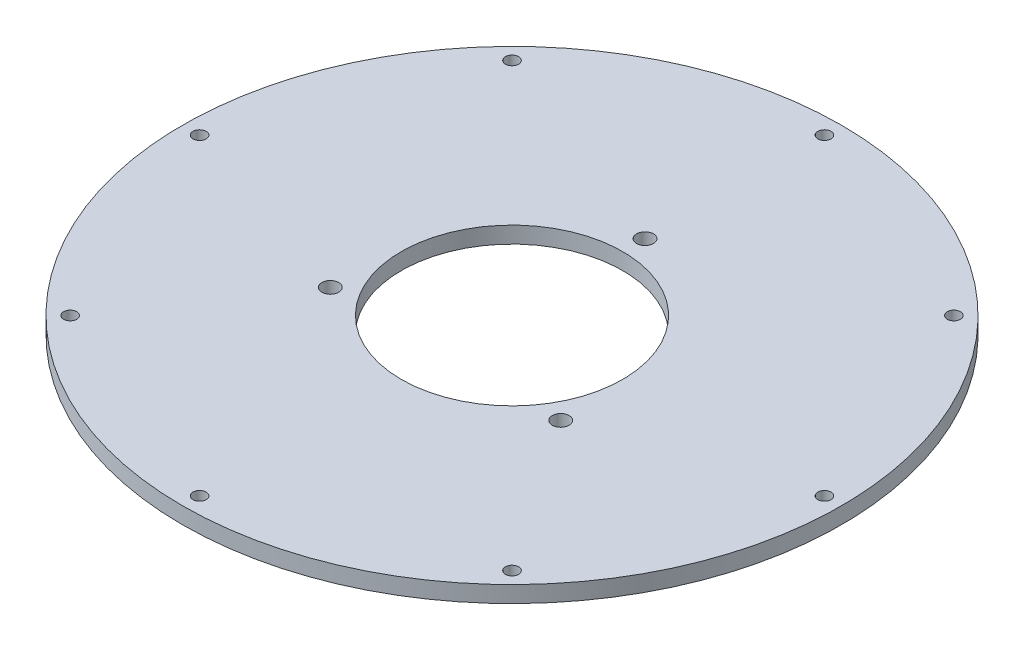
SolidWorks part; units mm, degrees
ref_plane "Front Plane" through (0, 0, 0) normal (0, 0, 1) x (1, 0, 0)
ref_plane "Top Plane" through (0, 0, 0) normal (0, 1, 0) x (1, 0, 0)
ref_plane "Right Plane" through (0, 0, 0) normal (1, 0, 0) x (0, 0, -1)
sketch "Sketch1" plane through (0, 0, 0) normal (0, 1, 0) x (1, 0, 0)
  circle A0 centre (0, 0) radius 62.5
  circle A1 centre (0, 0) radius 21
  circle A2 centre (0, 0) radius 21 construction
  dimension "D1" = 0
  dimension "D2" = 125
extrude "Boss-Extrude1" add sketch "Sketch1" along normal blind 3.125
sketch "Sketch2" plane through (0, 3.125, 0) normal (0, 1, 0) x (1, 0, 0)
  line L0 (0, 25.225) -> (0, 0) construction
  circle A0 centre (0, 25.225) radius 1.6
  circle A1 centre (21.8455, -12.6125) radius 1.6
  circle A2 centre (-21.8455, -12.6125) radius 1.6
  point P10 (0, 0)
  dimension "D2" = 3.2
  dimension "D3" = 3
extrude "Cut-Extrude1" cut sketch "Sketch2" against normal through all
sketch "Sketch5" plane through (0, 3.125, 0) normal (0, 1, 0) x (1, 0, 0)
  line L0 (3, 45.7275) -> (3, 31.607)
  line L1 (38.1011, 25.4618) -> (25.8724, 18.4016)
  line L2 (0, 0) -> (0, 62.5) construction
  line L3 (41.1011, -20.2657) -> (28.8724, -13.2054)
  line L4 (41.1011, 20.2657) -> (28.8724, 13.2054)
  line L5 (3, -45.7275) -> (3, -31.607)
  line L6 (38.1011, -25.4618) -> (25.8724, -18.4016)
  line L7 (-38.1011, -25.4618) -> (-25.8724, -18.4016)
  line L8 (-3, -45.7275) -> (-3, -31.607)
  line L9 (-41.1011, 20.2657) -> (-28.8724, 13.2054)
  line L10 (-41.1011, -20.2657) -> (-28.8724, -13.2054)
  line L11 (-3, 45.7275) -> (-3, 31.607)
  line L12 (-38.1011, 25.4618) -> (-25.8724, 18.4016)
  line L13 (3, 46.1306) -> (-3, 46.1306) construction
  circle A0 centre (0, 0) radius 62.5 construction
  arc A1 (4.6875, 29.6315) -> (23.3179, 18.8753) centre (0, 0) cw
  arc A2 (5.2174, 47.7156) -> (38.7142, 28.3762) centre (0, 0) cw
  arc A3 (38.7142, 28.3762) -> (38.1011, 25.4618) centre (37.1011, 27.1939) cw
  arc A4 (3, 45.7275) -> (5.2174, 47.7156) centre (5, 45.7275) cw
  arc A5 (23.3179, 18.8753) -> (25.8724, 18.4016) centre (24.8724, 20.1336) ccw
  arc A6 (3, 31.607) -> (4.6875, 29.6315) centre (5, 31.607) ccw
  arc A7 (28.0054, -10.7563) -> (28.8724, -13.2054) centre (29.8724, -11.4734) ccw
  arc A8 (43.9316, -19.3394) -> (41.1011, -20.2657) centre (42.1011, -18.5336) cw
  arc A9 (28.0054, 10.7563) -> (28.0054, -10.7563) centre (0, 0) cw
  arc A10 (28.8724, 13.2054) -> (28.0054, 10.7563) centre (29.8724, 11.4734) ccw
  arc A11 (41.1011, 20.2657) -> (43.9316, 19.3394) centre (42.1011, 18.5336) cw
  arc A12 (43.9316, 19.3394) -> (43.9316, -19.3394) centre (0, 0) cw
  arc A13 (4.6875, -29.6315) -> (3, -31.607) centre (5, -31.607) ccw
  arc A14 (5.2174, -47.7156) -> (3, -45.7275) centre (5, -45.7275) cw
  arc A15 (23.3179, -18.8753) -> (4.6875, -29.6315) centre (0, 0) cw
  arc A16 (25.8724, -18.4016) -> (23.3179, -18.8753) centre (24.8724, -20.1336) ccw
  arc A17 (38.1011, -25.4618) -> (38.7142, -28.3762) centre (37.1011, -27.1939) cw
  arc A18 (38.7142, -28.3762) -> (5.2174, -47.7156) centre (0, 0) cw
  arc A19 (-23.3179, -18.8753) -> (-25.8724, -18.4016) centre (-24.8724, -20.1336) ccw
  arc A20 (-38.7142, -28.3762) -> (-38.1011, -25.4618) centre (-37.1011, -27.1939) cw
  arc A21 (-4.6875, -29.6315) -> (-23.3179, -18.8753) centre (0, 0) cw
  arc A22 (-3, -31.607) -> (-4.6875, -29.6315) centre (-5, -31.607) ccw
  arc A23 (-3, -45.7275) -> (-5.2174, -47.7156) centre (-5, -45.7275) cw
  arc A24 (-5.2174, -47.7156) -> (-38.7142, -28.3762) centre (0, 0) cw
  arc A25 (-28.0054, 10.7563) -> (-28.8724, 13.2054) centre (-29.8724, 11.4734) ccw
  arc A26 (-43.9316, 19.3394) -> (-41.1011, 20.2657) centre (-42.1011, 18.5336) cw
  arc A27 (-28.0054, -10.7563) -> (-28.0054, 10.7563) centre (0, 0) cw
  arc A28 (-28.8724, -13.2054) -> (-28.0054, -10.7563) centre (-29.8724, -11.4734) ccw
  arc A29 (-41.1011, -20.2657) -> (-43.9316, -19.3394) centre (-42.1011, -18.5336) cw
  arc A30 (-43.9316, -19.3394) -> (-43.9316, 19.3394) centre (0, 0) cw
  arc A31 (-4.6875, 29.6315) -> (-3, 31.607) centre (-5, 31.607) ccw
  arc A32 (-5.2174, 47.7156) -> (-3, 45.7275) centre (-5, 45.7275) cw
  arc A33 (-23.3179, 18.8753) -> (-4.6875, 29.6315) centre (0, 0) cw
  arc A34 (-25.8724, 18.4016) -> (-23.3179, 18.8753) centre (-24.8724, 20.1336) ccw
  arc A35 (-38.1011, 25.4618) -> (-38.7142, 28.3762) centre (-37.1011, 27.1939) cw
  arc A36 (-38.7142, 28.3762) -> (-5.2174, 47.7156) centre (0, 0) cw
  point P80 (0, 0)
  point P82 (0, 46.1306)
  dimension "D1" = 2
  dimension "D4" = 30
  dimension "D5" = 48
  dimension "D3" = 6
  dimension "D2" = 6
extrude "Cut-Extrude2" [suppressed] cut sketch "Sketch5" against normal through all
sketch "Sketch6" plane through (0, 3.125, 0) normal (0, 1, 0) x (1, 0, 0)
  line L0 (59.25, 0) -> (-59.25, 0) construction
  line L1 (41.8961, -41.8961) -> (-41.8961, -41.8961) construction
  line L2 (41.8961, -41.8961) -> (41.8961, 41.8961) construction
  line L3 (41.8961, 41.8961) -> (-41.8961, 41.8961) construction
  line L4 (-41.8961, -41.8961) -> (-41.8961, 41.8961) construction
  line L5 (41.8961, -41.8961) -> (-41.8961, 41.8961) construction
  line L6 (41.8961, 41.8961) -> (-41.8961, -41.8961) construction
  line L7 (41.8961, 41.8961) -> (44.1942, 44.1942) construction
  line L8 (-59.25, 0) -> (-62.5, 0) construction
  line L9 (0, 0) -> (0, 59.25) construction
  line L10 (0, 0) -> (0, -59.25) construction
  circle A0 centre (-41.8961, 41.8961) radius 1.25
  circle A1 centre (41.8961, 41.8961) radius 1.25
  circle A2 centre (-41.8961, -41.8961) radius 1.25
  circle A3 centre (41.8961, -41.8961) radius 1.25
  circle A4 centre (-59.25, 0) radius 1.25
  circle A5 centre (59.25, 0) radius 1.25
  circle A6 centre (0, 0) radius 62.5 construction
  circle A7 centre (0, 0) radius 59.25 construction
  circle A8 centre (0, 59.25) radius 1.25
  circle A9 centre (0, -59.25) radius 1.25
  point P0 (0, 0)
  point P13 (0, 0)
  dimension "D2" = 2.5
  dimension "D4" = 2.5
  dimension "D1" = 3.25
  dimension "D3" = 3.25
extrude "Cut-Extrude3" cut sketch "Sketch6" against normal through all
equation "\"D3@Sketch6\"=\"D1@Sketch6\""
